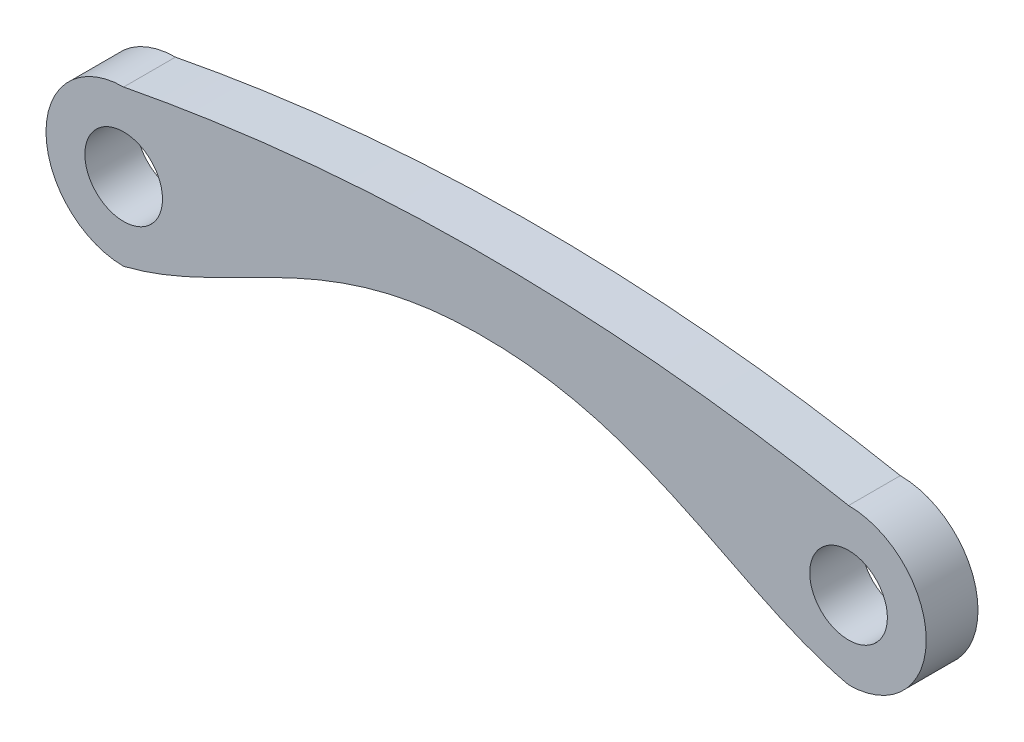
SolidWorks part; units mm, degrees
ref_plane "Front Plane" through (0, 0, 0) normal (0, 0, 1) x (1, 0, 0)
ref_plane "Top Plane" through (0, 0, 0) normal (0, 1, 0) x (1, 0, 0)
ref_plane "Right Plane" through (0, 0, 0) normal (1, 0, 0) x (0, 0, -1)
sketch "Sketch1" plane through (0, 0, 0) normal (0, 0, 1) x (1, 0, 0)
  circle A0 centre (-14, 0) radius 1.5
  circle A1 centre (14, 0) radius 1.5
  arc A2 (-14, 3) -> (-14, -3) centre (-14, 0) ccw
  arc A3 (14, -3) -> (14, 3) centre (14, 0) ccw
  spline S0 degree 3 poles (-14, -3) (-10.1108, -2.0255) (-6.3323, 1.6814) (6.359, 1.5796) (10.138, -2.1124) (14, -3) knots 0 0 0 0 0.449202 0.549202 1 1 1 1
  spline S1 degree 2 poles (-14, 3) (0, 5.7) (14, 3) knots 0 0 0 1 1 1
  point P4 (0, 0)
  point P11 (0, 4.3666)
  point P12 (0, 0)
  point P13 (0, 0)
  dimension "D3" = 3
  dimension "D4" = 6
  dimension "D5" = 1.6
  dimension "D1" = 14
  dimension "D2" = 14
  dimension "D6" = 2.75
extrude "Boss-Extrude1" add sketch "Sketch1" along normal blind 2
